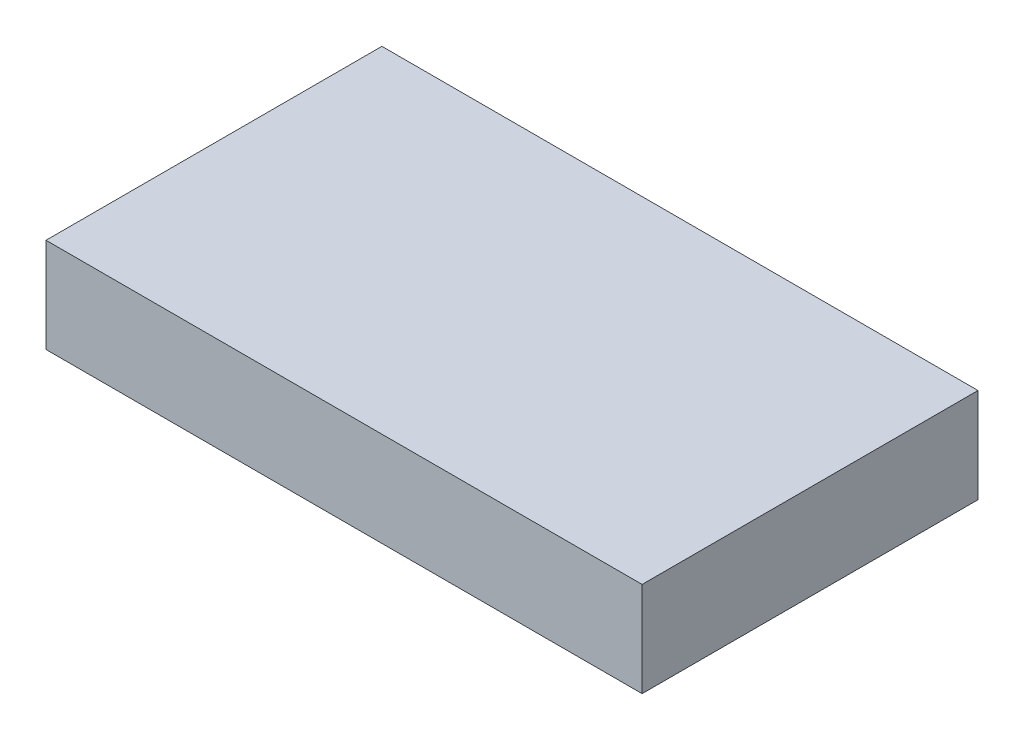
SolidWorks part; units mm, degrees
ref_plane "Front Plane" through (0, 0, 0) normal (0, 0, 1) x (1, 0, 0)
ref_plane "Top Plane" through (0, 0, 0) normal (0, 1, 0) x (1, 0, 0)
ref_plane "Right Plane" through (0, 0, 0) normal (1, 0, 0) x (0, 0, -1)
sketch "Sketch1" plane through (0, 0, 0) normal (0, 1, 0) x (1, 0, 0)
  line L1 (-63, -35.5) -> (63, -35.5)
  line L2 (-63, -35.5) -> (-63, 35.5)
  line L3 (-63, 35.5) -> (63, 35.5)
  line L4 (63, -35.5) -> (63, 35.5)
  line L5 (-63, -35.5) -> (63, 35.5) construction
  line L6 (-63, 35.5) -> (63, -35.5) construction
  point P0 (0, 0)
  dimension "D1" = 126
  dimension "D2" = 71
extrude "Boss-Extrude1" add sketch "Sketch1" along normal blind 20
